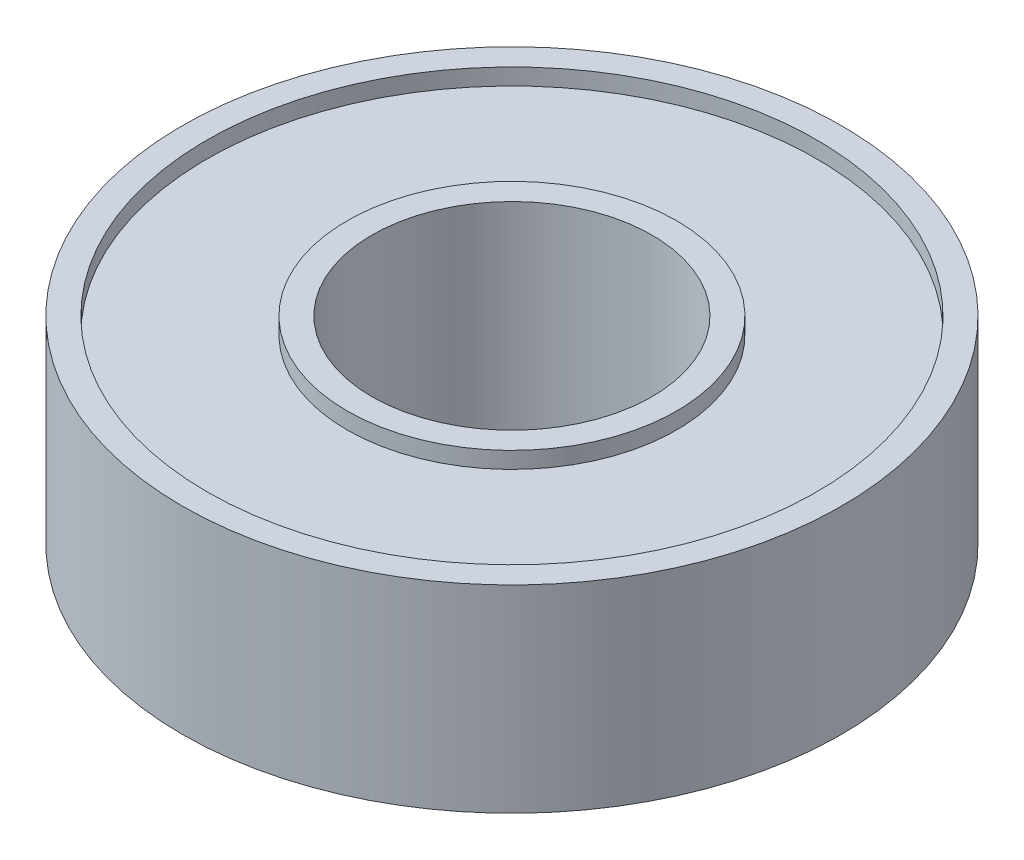
SolidWorks part; units mm, degrees
ref_plane "Front Plane" through (0, 0, 0) normal (0, 0, 1) x (1, 0, 0)
ref_plane "Top Plane" through (0, 0, 0) normal (0, 1, 0) x (1, 0, 0)
ref_plane "Right Plane" through (0, 0, 0) normal (1, 0, 0) x (0, 0, -1)
sketch "Sketch1" plane through (0, 0, 0) normal (0, 1, 0) x (1, 0, 0)
  circle A0 centre (0, 0) radius 20
  circle A1 centre (0, 0) radius 8.5
  dimension "D1" = 40
  dimension "D2" = 17
extrude "Boss-Extrude1" add sketch "Sketch1" along normal blind 12
sketch "Sketch2" plane through (0, 12, 0) normal (0, 1, 0) x (1, 0, 0)
  circle A0 centre (0, 0) radius 10
  circle A1 centre (0, 0) radius 18.5
  dimension "D1" = 20
  dimension "D2" = 37
extrude "Cut-Extrude1" cut sketch "Sketch2" against normal blind 1
sketch "Sketch3" plane through (0, 0, 0) normal (0, -1, 0) x (1, 0, 0)
  circle A0 centre (0, 0) radius 10
  circle A1 centre (0, 0) radius 18.5
  dimension "D1" = 20
  dimension "D2" = 37
extrude "Cut-Extrude2" cut sketch "Sketch3" against normal blind 1
